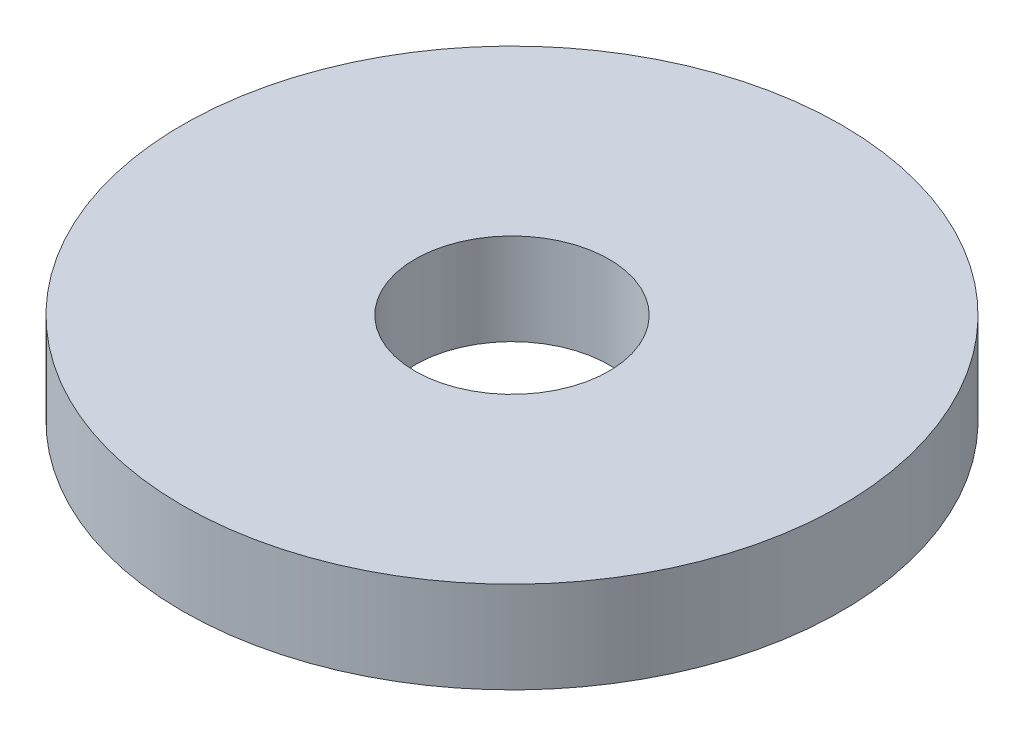
SolidWorks part; units mm, degrees
ref_plane "Front Plane" through (0, 0, 0) normal (0, 0, 1) x (1, 0, 0)
ref_plane "Top Plane" through (0, 0, 0) normal (0, 1, 0) x (1, 0, 0)
ref_plane "Right Plane" through (0, 0, 0) normal (1, 0, 0) x (0, 0, -1)
sketch "Sketch1" plane through (0, 0, 0) normal (0, 1, 0) x (1, 0, 0)
  circle A0 centre (0, 0) radius 9
  dimension "D1" = 18
extrude "Boss-Extrude1" add sketch "Sketch1" along normal blind 2.5
sketch "Sketch2" plane through (0, 2.5, 0) normal (0, 1, 0) x (1, 0, 0)
  circle A0 centre (0, 0) radius 2.65
  dimension "D1" = 5.3
extrude "Cut-Extrude1" cut sketch "Sketch2" against normal through all
